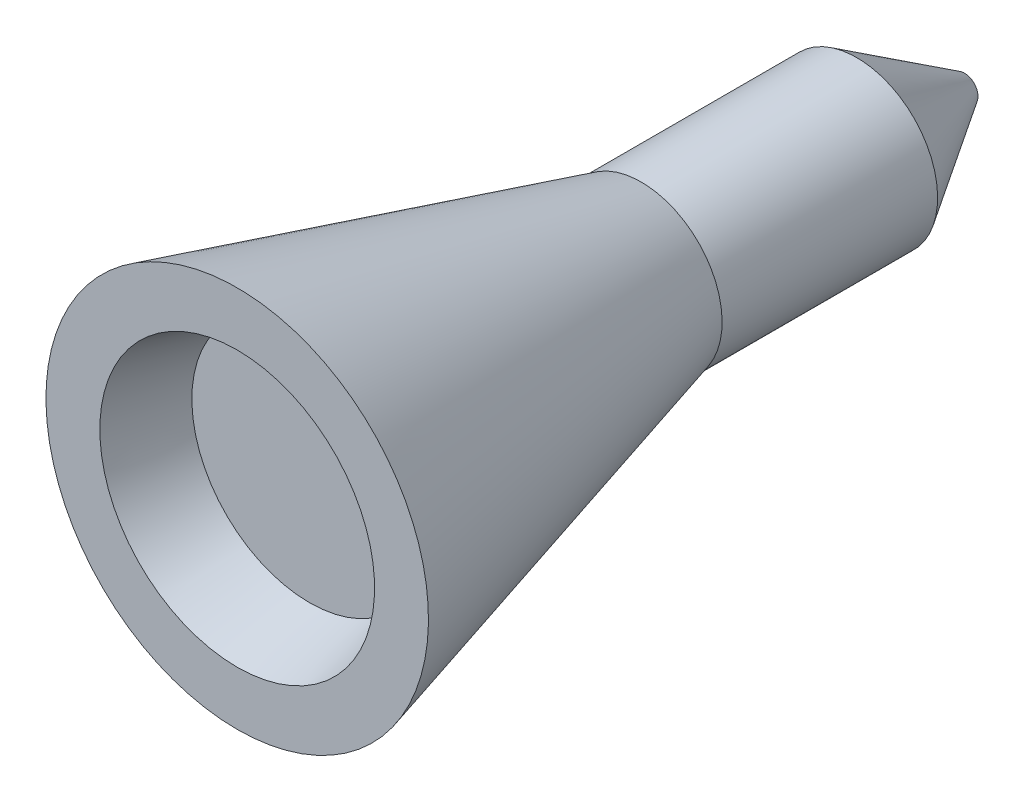
SolidWorks part; units mm, degrees
ref_plane "Front Plane" through (0, 0, 0) normal (0, 0, 1) x (1, 0, 0)
ref_plane "Top Plane" through (0, 0, 0) normal (0, 1, 0) x (1, 0, 0)
ref_plane "Right Plane" through (0, 0, 0) normal (1, 0, 0) x (0, 0, -1)
sketch "Sketch2" plane through (0, 0, 0) normal (1, 0, 0) x (0, 0, -1)
  line L0 (-5, 0) -> (-5, -3)
  line L1 (-5, -3) -> (15.3171, -3)
  line L2 (15.3171, -3) -> (15.3171, 0)
  line L3 (15.3171, 0) -> (-5, 0)
  line L4 (7.3171, 0) -> (-7.6829, 4.1)
  line L5 (-7.6829, 4.1) -> (-7.6829, 2.1)
  line L6 (-7.6829, 2.1) -> (0, 0)
  line L7 (0, 0) -> (7.3171, 0)
  line L8 (-5, 0) -> (-5, 1.3667)
  line L9 (-5, 1.3667) -> (0, 0)
  line L10 (15.3171, 0) -> (19.3171, -2.5)
  line L11 (19.3171, -2.5) -> (19.3171, -3)
  line L12 (19.3171, -3) -> (15.3171, -3)
  dimension "D1" = 8
  dimension "D2" = 7.1
  dimension "D3" = 3
  dimension "D4" = 15
  dimension "D5" = 2
  dimension "D6" = 5
  dimension "D7" = 0.5
  dimension "D8" = 4
revolve "Revolve1" add sketch "Sketch2" angle 360 about L1
